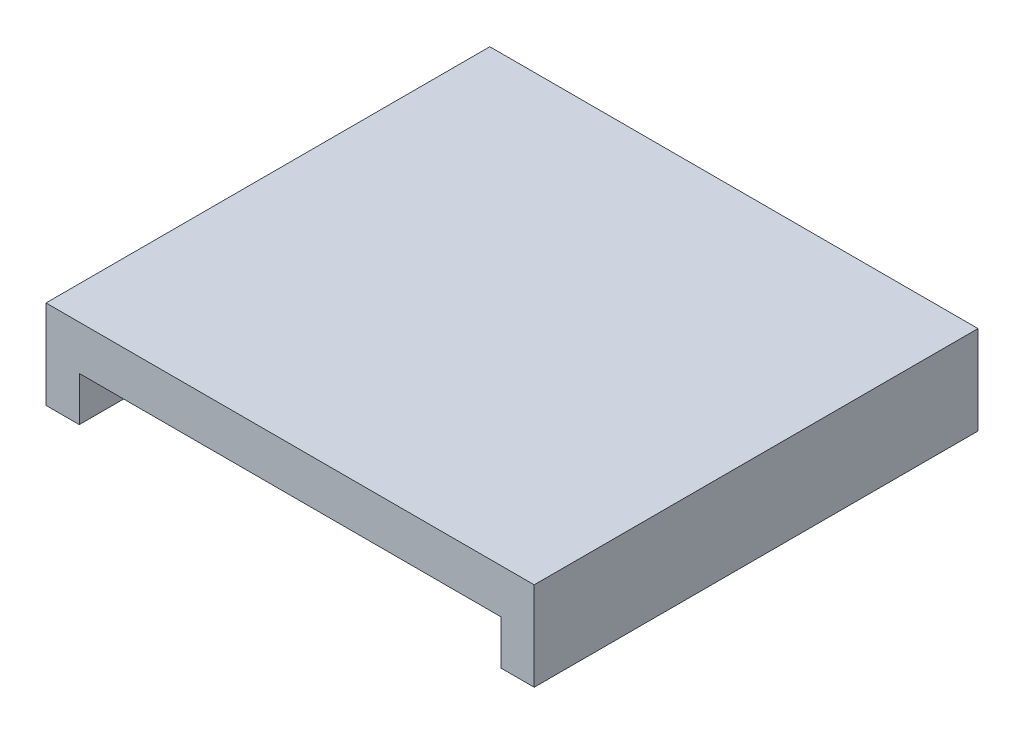
SolidWorks part; units mm, degrees
ref_plane "Front Plane" through (0, 0, 0) normal (0, 0, 1) x (1, 0, 0)
ref_plane "Top Plane" through (0, 0, 0) normal (0, 1, 0) x (1, 0, 0)
ref_plane "Right Plane" through (0, 0, 0) normal (1, 0, 0) x (0, 0, -1)
sketch "Sketch2" plane through (0, 0, 0) normal (0, 1, 0) x (1, 0, 0)
  line L1 (110, 100) -> (-110, 100)
  line L2 (110, 100) -> (110, -100)
  line L3 (110, -100) -> (-110, -100)
  line L4 (-110, 100) -> (-110, -100)
  line L5 (110, 100) -> (-110, -100) construction
  line L6 (110, -100) -> (-110, 100) construction
  point P0 (0, 0)
  dimension "D1" = 200
  dimension "D2" = 220
extrude "Boss-Extrude1" add sketch "Sketch2" along normal blind 20
sketch "Sketch3" plane through (0, 0, 0) normal (0, -1, 0) x (1, 0, 0)
  line L0 (0, 0) -> (0, 41.393) construction
  line L1 (110, -100) -> (-110, -100) construction
  line L2 (-110, 100) -> (-95, 100)
  line L3 (-110, 100) -> (-110, -100)
  line L4 (-110, -100) -> (-95, -100)
  line L5 (-95, 100) -> (-95, -100)
  line L6 (-102.5, -100) -> (-102.5, 100) construction
  line L7 (-110, 0) -> (-95, 0) construction
  line L8 (110, -100) -> (95, -100)
  line L9 (95, 100) -> (95, -100)
  line L10 (110, 100) -> (95, 100)
  line L11 (110, 100) -> (110, -100)
  line L12 (110, 0) -> (95, 0) construction
  line L13 (102.5, -100) -> (102.5, 100) construction
  point P13 (102.5, 0)
  point P247 (-102.5, 0)
  dimension "D1" = 15
extrude "Boss-Extrude2" add sketch "Sketch3" along normal blind 20
